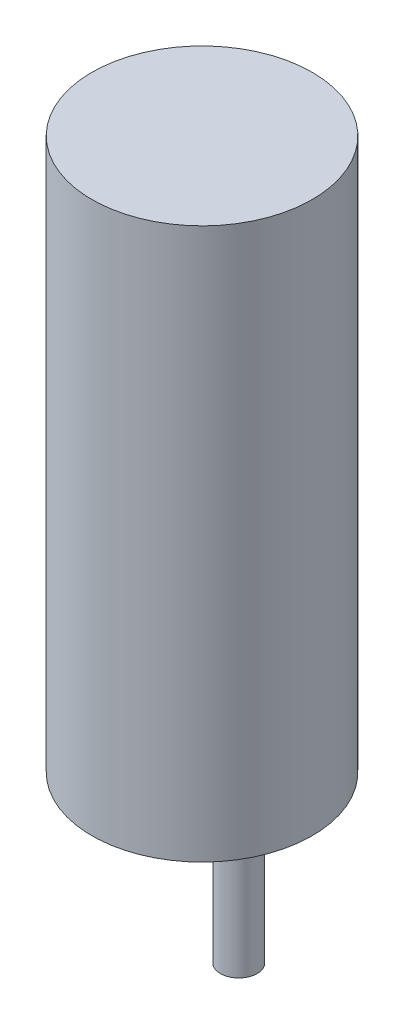
SolidWorks part; units mm, degrees
ref_plane "Front Plane" through (0, 0, 0) normal (0, 0, 1) x (1, 0, 0)
ref_plane "Top Plane" through (0, 0, 0) normal (0, 1, 0) x (1, 0, 0)
ref_plane "Right Plane" through (0, 0, 0) normal (1, 0, 0) x (0, 0, -1)
sketch "Sketch1" plane through (0, 0, 0) normal (0, 1, 0) x (1, 0, 0)
  circle A0 centre (0, 0) radius 18
extrude "Boss-Extrude1" add sketch "Sketch1" along normal blind 90
sketch "Sketch2" plane through (0, 0, 0) normal (0, -1, 0) x (1, 0, 0)
  circle A0 centre (0, -6) radius 3
extrude "Boss-Extrude2" add sketch "Sketch2" along normal blind 30 contours A0
